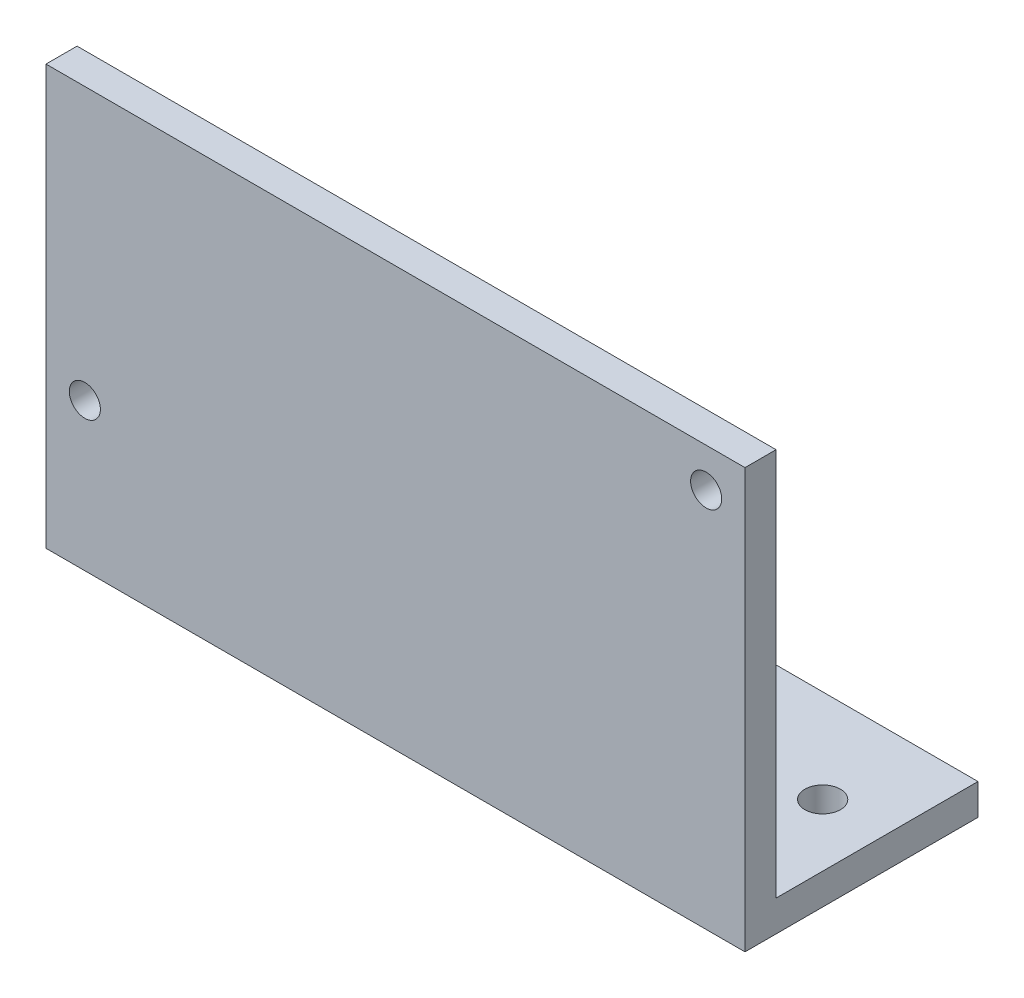
SolidWorks part; units mm, degrees
ref_plane "Front Plane" through (0, 0, 0) normal (0, 0, 1) x (1, 0, 0)
ref_plane "Top Plane" through (0, 0, 0) normal (0, 1, 0) x (1, 0, 0)
ref_plane "Right Plane" through (0, 0, 0) normal (1, 0, 0) x (0, 0, -1)
sketch "Sketch1" plane through (0, 0, 0) normal (0, 0, 1) x (1, 0, 0)
  line L0 (-22.5, 12.5) -> (-22.5, -12.5)
  line L1 (-22.5, 12.5) -> (22.5, 12.5)
  line L2 (-22.5, -12.5) -> (22.5, -12.5)
  line L3 (22.5, 12.5) -> (22.5, -12.5)
  line L4 (-22.5, -12.5) -> (-22.5, -14.5)
  line L5 (-22.5, -14.5) -> (22.5, -14.5)
  line L6 (22.5, -14.5) -> (22.5, -12.5)
  dimension "D1" = 45
  dimension "D2" = 25
  dimension "D3" = 12.5
  dimension "D4" = 22.5
  dimension "D5" = 2
extrude "Boss-Extrude3" add sketch "Sketch1" along normal blind 2 contours L3 L1 L0 L2 | L5 L6 L2 L4
sketch "Sketch6" plane through (0, 0, 2) normal (0, 0, 1) x (1, 0, 0)
  line L0 (-22.5, -12.5) -> (-22.5, -14.5)
  line L1 (-22.5, -14.5) -> (22.5, -14.5)
  line L2 (22.5, -14.5) -> (22.5, -12.5)
  line L3 (22.5, -12.5) -> (-22.5, -12.5)
extrude "Boss-Extrude4" add sketch "Sketch6" against normal blind 15
sketch "Sketch7" plane through (0, 0, 0) normal (0, 0, -1) x (-1, 0, 0)
  line L0 (-22.5, 12.5) -> (-22.5, -12.5) construction
  line L1 (22.5, 12.5) -> (-22.5, 12.5) construction
  line L2 (22.5, 12.5) -> (22.5, -12.5) construction
  circle A0 centre (-20, 10) radius 1
  circle A1 centre (20, -5) radius 1
  dimension "D1" = 2.5
  dimension "D2" = 2.5
  dimension "D3" = 17.5
  dimension "D4" = 2.5
extrude "Cut-Extrude1" cut sketch "Sketch7" against normal blind 18
sketch "Sketch9" plane through (0, -12.5, 0) normal (0, 1, 0) x (1, 0, 0)
  line L0 (22.5, 13) -> (-22.5, 13) construction
  line L1 (-22.5, 13) -> (-22.5, 0) construction
  line L2 (22.5, 13) -> (22.5, 0) construction
  circle A0 centre (-18.5, 7) radius 1
  circle A1 centre (18.5, 7) radius 1.1445
  dimension "D1" = 6
  dimension "D2" = 6
  dimension "D3" = 4
  dimension "D4" = 4
extrude "Cut-Extrude3" cut sketch "Sketch9" against normal blind 18
scale "Scale1" scale about centroid uniform scaling yes scale factor 0.75
